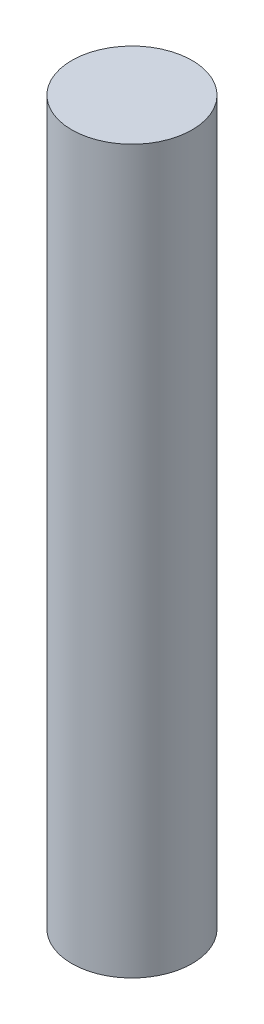
SolidWorks part; units mm, degrees
ref_plane "Front Plane" through (0, 0, 0) normal (0, 0, 1) x (1, 0, 0)
ref_plane "Top Plane" through (0, 0, 0) normal (0, 1, 0) x (1, 0, 0)
ref_plane "Right Plane" through (0, 0, 0) normal (1, 0, 0) x (0, 0, -1)
sketch "Sketch1" plane through (0, 0, 0) normal (0, 1, 0) x (1, 0, 0)
  circle A0 centre (-2.4479, -0.958) radius 2.5
  dimension "D1" = 5
extrude "Boss-Extrude1" add sketch "Sketch1" against normal blind 30
